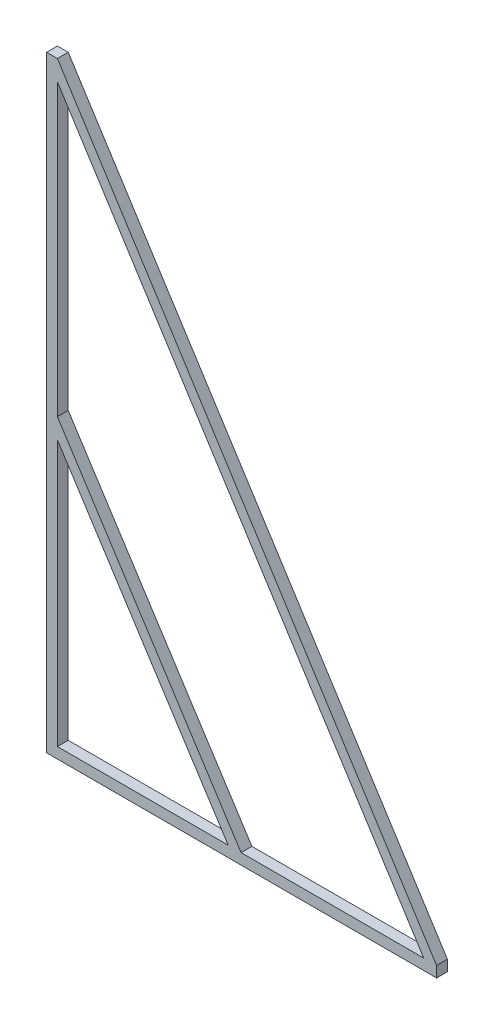
SolidWorks part; units mm, degrees
ref_plane "Front Plane" through (0, 0, 0) normal (0, 0, 1) x (1, 0, 0)
ref_plane "Top Plane" through (0, 0, 0) normal (0, 1, 0) x (1, 0, 0)
ref_plane "Right Plane" through (0, 0, 0) normal (1, 0, 0) x (0, 0, -1)
sketch "Sketch1" plane through (0, 0, 0) normal (0, 0, 1) x (1, 0, 0)
  line L0 (0, 140) -> (90, 0) construction
  line L1 (89.7577, 5) -> (174.0735, 5)
  line L2 (0, 0) -> (0, 280)
  line L3 (0, 280) -> (5, 280)
  line L4 (5, 5) -> (5, 127.5991)
  line L5 (0, 0) -> (180, 0)
  line L6 (5, 136.8454) -> (89.7577, 5)
  line L7 (5, 5) -> (83.8137, 5)
  line L8 (180, 0) -> (180, 5)
  line L9 (5, 280) -> (180, 5)
  line L10 (5, 270.6869) -> (174.0735, 5)
  line L11 (5, 127.5991) -> (83.8137, 5)
  line L12 (83.8137, 5) -> (85.9166, 6.3519) construction
  line L13 (85.9166, 6.3519) -> (88.0196, 7.7038) construction
  line L14 (5, 136.8454) -> (5, 270.6869)
  dimension "D1" = 280
  dimension "D2" = 180
  dimension "D3" = 5
  dimension "D4" = 5
  dimension "D5" = 5
  dimension "D6" = 5
extrude "Boss-Extrude1" add sketch "Sketch1" along normal blind 5
